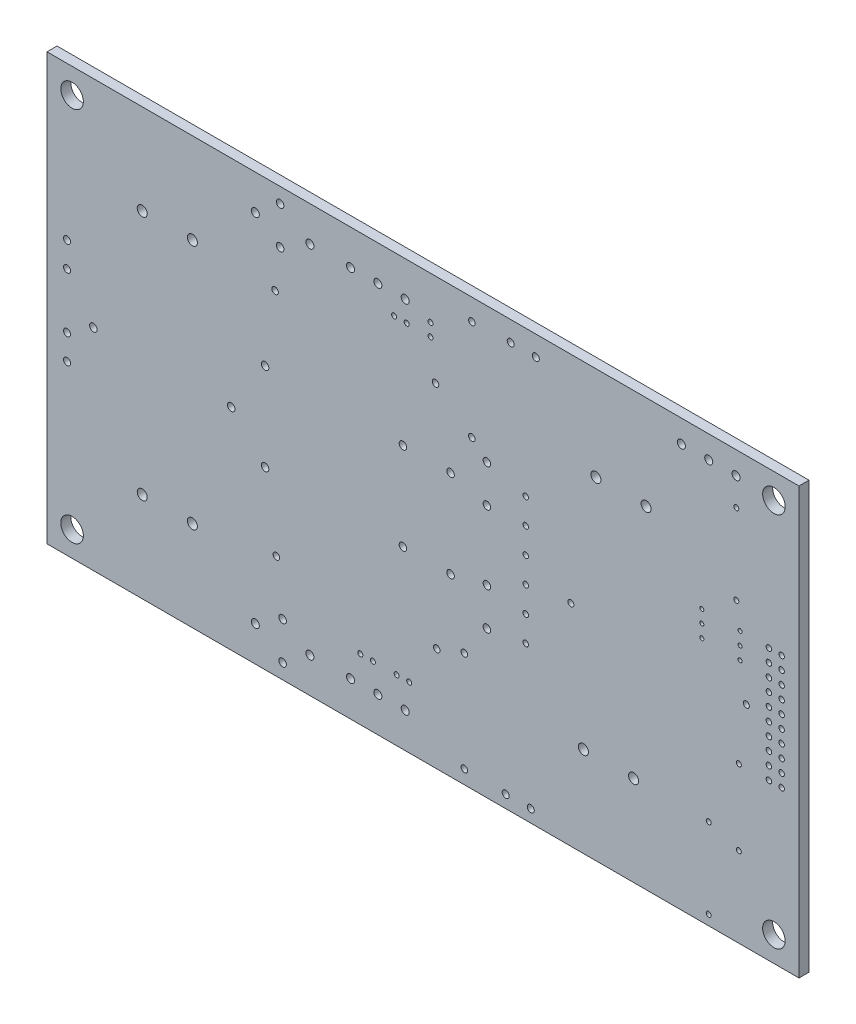
SolidWorks part; units mm, degrees
ref_plane "Спереди" through (0, 0, 0) normal (0, 0, 1) x (1, 0, 0)
ref_plane "Сверху" through (0, 0, 0) normal (0, 1, 0) x (1, 0, 0)
ref_plane "Справа" through (0, 0, 0) normal (1, 0, 0) x (0, 0, -1)
sketch "Эскиз1" plane through (0, 0, 0) normal (0, 0, 1) x (1, 0, 0)
  line L0 (-22.6071, 0) -> (23.7373, 0) construction
  line L1 (-75, -42.5) -> (75, -42.5)
  line L2 (-75, -42.5) -> (-75, 42.5)
  line L3 (-75, 42.5) -> (75, 42.5)
  line L4 (75, -42.5) -> (75, 42.5)
  line L5 (0, 0) -> (0, 31.6453) construction
  circle A0 centre (-70, -37.5) radius 2.25
  circle A1 centre (70, -37.5) radius 2.25
  circle A2 centre (70, 37.5) radius 2.25
  circle A3 centre (-70, 37.5) radius 2.25
  dimension "D3" = 4.5
  dimension "D1" = 150
  dimension "D2" = 85
  dimension "D4" = 5
  dimension "D5" = 5
extrude "Вытянуть1" add sketch "Эскиз1" along normal blind 2
sketch "Эскиз2" plane through (0, 0, 2) normal (0, 0, 1) x (1, 0, 0)
  line L0 (-75, 42.5) -> (-75, -42.5) construction
  line L1 (-75, -42.5) -> (75, -42.5) construction
  line L2 (-33.45, 35.5) -> (-22.55, 35.5) construction
  line L3 (-14.45, -35.5) -> (-3.55, -35.5) construction
  line L4 (69, 11.5) -> (71.54, 11.5) construction
  line L5 (20.5, -11.95) -> (53.2663, -11.95) construction
  line L6 (20.5, -11.95) -> (32.9466, 0.4966) construction
  line L7 (51.55, 38) -> (62.45, 38) construction
  line L14 (63, -26.5) -> (63, -11.5) construction
  line L15 (-14.45, 35.5) -> (-3.55, 35.5) construction
  line L16 (-33.45, -35.5) -> (-22.55, -35.5) construction
  line L18 (20.5, -22.58) -> (20.5, -11.95) construction
  circle A0 centre (69, 11.5) radius 0.55
  circle A1 centre (71.54, 11.5) radius 0.55
  circle A2 centre (69, 8.96) radius 0.55
  circle A3 centre (71.54, 8.96) radius 0.55
  circle A4 centre (69, 6.42) radius 0.55
  circle A5 centre (71.54, 6.42) radius 0.55
  circle A6 centre (69, 3.88) radius 0.55
  circle A7 centre (71.54, 3.88) radius 0.55
  circle A8 centre (69, 1.34) radius 0.55
  circle A9 centre (71.54, 1.34) radius 0.55
  circle A10 centre (69, -1.2) radius 0.55
  circle A11 centre (71.54, -1.2) radius 0.55
  circle A12 centre (69, -3.74) radius 0.55
  circle A13 centre (71.54, -3.74) radius 0.55
  circle A14 centre (69, -6.28) radius 0.55
  circle A15 centre (71.54, -6.28) radius 0.55
  circle A16 centre (69, -8.82) radius 0.55
  circle A17 centre (71.54, -8.82) radius 0.55
  circle A18 centre (69, -11.36) radius 0.55
  circle A19 centre (71.54, -11.36) radius 0.55
  circle A20 centre (63, -26.5) radius 0.5
  circle A21 centre (63, -11.5) radius 0.5
  circle A22 centre (-14.45, 35.5) radius 0.8
  circle A23 centre (-9, 35.5) radius 0.8
  circle A24 centre (-3.55, 35.5) radius 0.8
  circle A25 centre (-33.45, 35.5) radius 0.8
  circle A26 centre (51.55, 38) radius 0.8
  circle A27 centre (-22.55, 35.5) radius 0.8
  circle A28 centre (-33.45, -35.5) radius 0.8
  circle A29 centre (57, 38) radius 0.8
  circle A30 centre (-22.55, -35.5) radius 0.8
  circle A31 centre (-14.45, -35.5) radius 0.8
  circle A32 centre (-9, -35.5) radius 0.8
  circle A33 centre (-3.55, -35.5) radius 0.8
  circle A34 centre (62.45, 38) radius 0.8
  circle A37 centre (20.5, 13.45) radius 0.55
  circle A38 centre (20.5, 8.37) radius 0.55
  circle A39 centre (20.5, -1.79) radius 0.55
  circle A40 centre (20.5, 3.29) radius 0.55
  circle A41 centre (20.5, -6.87) radius 0.55
  circle A45 centre (20.5, -11.95) radius 0.55
  dimension "D3" = 1.1
  dimension "D4" = 2.54
  dimension "D7" = 1
  dimension "D8" = 138
  dimension "D9" = 60.55
  dimension "D10" = 10.9
  dimension "D11" = 1.1
  dimension "D12" = 78
  dimension "D13" = 1.6
  dimension "D19" = 1.6
  dimension "D20" = 5.45
  dimension "D23" = 10.9
  dimension "D14" = 10.9
  dimension "D26" = 10.9
  dimension "D27" = 80.5
  dimension "D28" = 126.55
  dimension "D30" = 5.08
  dimension "D32" = 30.55
  dimension "D6" = 15
  dimension "D33" = 5.08
  dimension "D34" = 5.08
  dimension "D36" = 5.08
  dimension "D42" = 1.6
  dimension "D24" = 54
  dimension "D35" = 5.08
  dimension "D1" = 144
  dimension "D5" = 16
  dimension "D15" = 41.55
  dimension "D16" = 78
  dimension "D17" = 7
  dimension "D18" = 7
  dimension "D21" = 41.55
  dimension "D22" = 60.55
  dimension "D25" = 45
  dimension "D31" = 95.5
extrude "Вырез-Вытянуть1" cut sketch "Эскиз2" against normal blind 2
sketch "Эскиз3" plane through (0, 0, 2) normal (0, 0, 1) x (1, 0, 0)
  line L0 (-75, -42.5) -> (75, -42.5) construction
  line L1 (-75, 42.5) -> (-75, -42.5) construction
  line L2 (-56, 24.5) -> (-46, 24.5) construction
  line L6 (16.5, -40) -> (21.5, -40) construction
  line L7 (-71, 7) -> (-71, 12) construction
  line L8 (-71, -9) -> (-71, -4) construction
  line L9 (-75, -42.5) -> (75, -42.5) construction
  line L12 (57, -40.5) -> (57, -24.5) construction
  line L14 (47.25, 45) -> (47.25, 55) construction
  line L16 (34.5, 23.75) -> (44.5, 23.75) construction
  line L17 (32, -24.5) -> (42, -24.5) construction
  line L18 (-56, -24.5) -> (-46, -24.5) construction
  line L19 (62.5, 16.5) -> (62.5, 32.5) construction
  line L20 (63.24, 11.58) -> (63.24, 6.5) construction
  line L21 (55.62, 6.5) -> (55.62, 12.7862) construction
  line L22 (55.62, 6.5) -> (63.24, 6.5) construction
  line L23 (54, 39.5) -> (60, 39.5) construction
  line L24 (17.5, 38.5) -> (22.5, 38.5) construction
  line L25 (29.5, -0.5) -> (64.5, -0.5) construction
  circle A0 centre (-56, 24.5) radius 1
  circle A1 centre (-46, 24.5) radius 1
  circle A2 centre (-56, -24.5) radius 1
  circle A3 centre (-46, -24.5) radius 1
  circle A10 centre (16.5, -40) radius 0.7
  circle A12 centre (21.5, -40) radius 0.7
  circle A13 centre (-71, 7) radius 0.7
  circle A14 centre (-71, 12) radius 0.7
  circle A15 centre (-71, -9) radius 0.7
  circle A16 centre (-71, -4) radius 0.7
  circle A20 centre (57, -40.5) radius 0.5
  circle A21 centre (57, -24.5) radius 0.5
  circle A28 centre (34.5, 23.75) radius 1
  circle A29 centre (44.5, 23.75) radius 1
  circle A30 centre (32, -24.5) radius 1
  circle A31 centre (42, -24.5) radius 1
  circle A35 centre (17.5, 38.5) radius 0.7
  circle A36 centre (62.5, 16.5) radius 0.5
  circle A37 centre (62.5, 32.5) radius 0.5
  circle A38 centre (63.24, 11.58) radius 0.4
  circle A39 centre (63.24, 6.5) radius 0.4
  circle A40 centre (55.62, 9.04) radius 0.4
  circle A41 centre (63.24, 9.04) radius 0.4
  circle A42 centre (55.62, 6.5) radius 0.4
  circle A43 centre (55.62, 11.58) radius 0.4
  circle A44 centre (22.5, 38.5) radius 0.7
  circle A45 centre (64.5, -0.5) radius 0.6
  circle A46 centre (29.5, -0.5) radius 0.6
  dimension "D9" = 75
  dimension "D16" = 91.5
  dimension "D17" = 5
  dimension "D18" = 49.5
  dimension "D22" = 1.2
  dimension "D23" = 1.2
  dimension "D28" = 1
  dimension "D44" = 10
  dimension "D14" = 5
  dimension "D15" = 2.5
  dimension "D30" = 16
  dimension "D35" = 10
  dimension "D20" = 1.4
  dimension "D50" = 1.4
  dimension "D56" = 19
  dimension "D58" = 18
  dimension "D59" = 16
  dimension "D63" = 7.62
  dimension "D64" = 2.54
  dimension "D65" = 5.08
  dimension "D67" = 130.62
  dimension "D76" = 5
  dimension "D77" = 1.4
  dimension "D78" = 35
  dimension "D19" = 4
  dimension "D21" = 5
  dimension "D29" = 2
  dimension "D31" = 132
  dimension "D34" = 10
  dimension "D38" = 122.25
  dimension "D45" = 66.25
  dimension "D46" = 109.5
  dimension "D47" = 10
  dimension "D48" = 18
  dimension "D49" = 107
  dimension "D51" = 4
  dimension "D52" = 33.5
  dimension "D57" = 67
  dimension "D60" = 137.5
  dimension "D62" = 5.08
  dimension "D66" = 49
  dimension "D68" = 19
  dimension "D71" = 82
  dimension "D74" = 81
  dimension "D75" = 92.5
  dimension "D79" = 42
  dimension "D80" = 104.5
extrude "Вырез-Вытянуть2" cut sketch "Эскиз3" against normal blind 10
sketch "Эскиз4" plane through (0, 0, 2) normal (0, 0, 1) x (1, 0, 0)
  line L0 (-41.37, -35.5) -> (-19.37, -35.5) construction
  line L1 (-75, 42.5) -> (-75, -42.5) construction
  line L2 (-75, -42.5) -> (75, -42.5) construction
  line L3 (-14.5, 31.75) -> (-3.5, 31.75) construction
  line L4 (-29.5, 24) -> (2.5, 24) construction
  line L5 (-65.75, -0.5) -> (-38.25, -0.5) construction
  line L6 (8.25, -39.75) -> (8.25, -19.75) construction
  line L7 (-14.25, -31.5) -> (-3.25, -31.5) construction
  line L8 (-28.5, 32) -> (-28.5, 39.5) construction
  line L9 (9.75, 18.25) -> (9.75, 38.25) construction
  line L10 (-28, -39.5) -> (-28, -32) construction
  line L11 (-31.5, 10) -> (-4, 10) construction
  line L12 (12.75, -13.25) -> (12.75, -5.75) construction
  line L13 (12.75, 8) -> (12.75, 15.5) construction
  line L15 (-31.5, -7.5) -> (-4, -7.5) construction
  line L16 (-29.25, -21.75) -> (2.75, -21.75) construction
  circle A0 centre (12.75, -5.75) radius 0.75
  circle A2 centre (-29.5, 24) radius 0.65
  circle A3 centre (12.75, -13.25) radius 0.75
  circle A4 centre (5.5, 10) radius 0.75
  circle A6 centre (2.5, 24) radius 0.65
  circle A7 centre (12.75, 15.5) radius 0.75
  circle A8 centre (5.5, -7.5) radius 0.75
  circle A9 centre (-65.75, -0.5) radius 0.75
  circle A10 centre (12.75, 8) radius 0.75
  circle A11 centre (8.25, -39.75) radius 0.65
  circle A12 centre (8.25, -19.75) radius 0.65
  circle A13 centre (-38.25, -0.5) radius 0.75
  circle A15 centre (9.75, 18.25) radius 0.65
  circle A16 centre (9.75, 38.25) radius 0.65
  circle A18 centre (-28.5, 39.5) radius 0.75
  circle A19 centre (-31.5, 10) radius 0.75
  circle A20 centre (-4, 10) radius 0.75
  circle A21 centre (-28.5, 32) radius 0.75
  circle A22 centre (-28, -32) radius 0.75
  circle A23 centre (-28, -39.5) radius 0.75
  circle A40 centre (-31.5, -7.5) radius 0.75
  circle A41 centre (-4, -7.5) radius 0.75
  circle A42 centre (-29.25, -21.75) radius 0.65
  circle A43 centre (2.75, -21.75) radius 0.65
  dimension "D10" = 32
  dimension "D12" = 66.5
  dimension "D15" = 60.5
  dimension "D19" = 83.25
  dimension "D24" = 1.3
  dimension "D25" = 27.5
  dimension "D26" = 1.3
  dimension "D29" = 1.3
  dimension "D31" = 37
  dimension "D37" = 27.5
  dimension "D39" = 43.5
  dimension "D40" = 52.5
  dimension "D42" = 46.5
  dimension "D52" = 87.75
  dimension "D55" = 87.75
  dimension "D72" = 32
  dimension "D74" = 45.75
  dimension "D44" = 7.5
  dimension "D13" = 20
  dimension "D18" = 2.75
  dimension "D20" = 1.5
  dimension "D22" = 84.75
  dimension "D23" = 60.75
  dimension "D27" = 35
  dimension "D28" = 43.5
  dimension "D30" = 1.5
  dimension "D16" = 74.25
  dimension "D17" = 1.3
  dimension "D34" = 37
  dimension "D35" = 9.25
  dimension "D36" = 42
  dimension "D21" = 20
  dimension "D33" = 1.5
  dimension "D8" = 1.3
  dimension "D43" = 82
  dimension "D45" = 1.5
  dimension "D48" = 7.5
  dimension "D11" = 45.5
  dimension "D32" = 27.5
  dimension "D46" = 47
  dimension "D47" = 3
  dimension "D50" = 7.5
  dimension "D51" = 7.5
  dimension "D53" = 29.25
  dimension "D54" = 50.5
  dimension "D67" = 20.75
extrude "Вырез-Вытянуть3" cut sketch "Эскиз4" against normal blind 10
sketch "Эскиз5" plane through (0, 0, 2) normal (0, 0, 1) x (1, 0, 0)
  line L0 (1.5, 31.5) -> (1.5, 34) construction
  line L1 (-5.75, 31.5) -> (-3.25, 31.5) construction
  line L2 (-75, -42.5) -> (75, -42.5) construction
  line L3 (-75, 42.5) -> (-75, -42.5) construction
  line L4 (-12.5, -30.25) -> (-10, -30.25) construction
  line L5 (-5.25, -30.25) -> (-2.75, -30.25) construction
  line L6 (-75, -42.5) -> (75, -42.5) construction
  line L7 (-3.25, 31.5) -> (1.5, 31.5) construction
  circle A0 centre (1.5, 34) radius 0.5
  circle A1 centre (1.5, 31.5) radius 0.5
  circle A2 centre (-5.75, 31.5) radius 0.5
  circle A3 centre (-3.25, 31.5) radius 0.5
  circle A4 centre (-5.25, -30.25) radius 0.5
  circle A5 centre (-2.75, -30.25) radius 0.5
  circle A6 centre (-10, -30.25) radius 0.5
  circle A7 centre (-12.5, -30.25) radius 0.5
  dimension "D2" = 1
  dimension "D3" = 2.5
  dimension "D6" = 74
  dimension "D7" = 76.5
  dimension "D9" = 1
  dimension "D4" = 2.5
  dimension "D15" = 76.5
  dimension "D11" = 62.5
  dimension "D5" = 69.25
  dimension "D8" = 2.5
  dimension "D10" = 2.5
  dimension "D12" = 69.75
  dimension "D13" = 12.25
extrude "Вырез-Вытянуть4" cut sketch "Эскиз5" against normal blind 10
